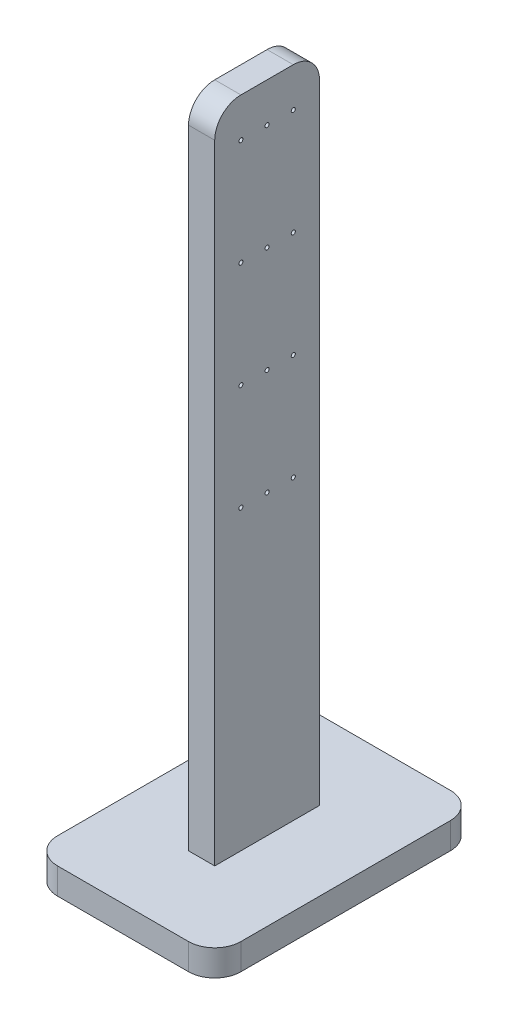
SolidWorks part; units mm, degrees
material "尼龙 101"
ref_plane "前视基准面" through (0, 0, 0) normal (0, 0, 1) x (1, 0, 0)
ref_plane "上视基准面" through (0, 0, 0) normal (0, 1, 0) x (1, 0, 0)
ref_plane "右视基准面" through (0, 0, 0) normal (1, 0, 0) x (0, 0, -1)
sketch "草图1" plane through (0, 0, 0) normal (1, 0, 0) x (0, 0, -1)
  line L1 (0, 0) -> (40, 0)
  line L2 (0, 0) -> (0, 240)
  line L3 (10, 250) -> (30, 250)
  line L4 (40, 0) -> (40, 240)
  circle A0 centre (10, 235) radius 0.7835
  circle A1 centre (20, 235) radius 0.7835
  circle A2 centre (30, 235) radius 0.7835
  arc A3 (30, 250) -> (40, 240) centre (30, 240) cw
  arc A4 (0, 240) -> (10, 250) centre (10, 240) cw
  circle A5 centre (10, 194.5) radius 0.7835
  circle A6 centre (20, 194.5) radius 0.7835
  circle A7 centre (30, 194.5) radius 0.7835
  circle A8 centre (10, 154) radius 0.7835
  circle A9 centre (20, 154) radius 0.7835
  circle A10 centre (30, 154) radius 0.7835
  circle A11 centre (10, 113.5) radius 0.7835
  circle A12 centre (20, 113.5) radius 0.7835
  circle A13 centre (30, 113.5) radius 0.7835
  point P17 (0, 250)
  dimension "D3" = 1.567
  dimension "D8" = 10
  dimension "D1" = 250
  dimension "D2" = 40
  dimension "D5" = 10
  dimension "D6" = 15
  dimension "D7" = 10
  dimension "D10" = 40.5
  dimension "D4" = 3
  dimension "D9" = 4
extrude "凸台-拉伸1" add sketch "草图1" along normal blind 10
cosmetic thread "装饰螺纹线1" parameters "D2"=2
cosmetic thread "装饰螺纹线2" parameters "D2"=2
cosmetic thread "装饰螺纹线3" parameters "D2"=2
cosmetic thread "装饰螺纹线4" parameters "D2"=2
cosmetic thread "装饰螺纹线5" parameters "D2"=2
cosmetic thread "装饰螺纹线6" parameters "D2"=2
cosmetic thread "装饰螺纹线7" parameters "D2"=2
cosmetic thread "装饰螺纹线8" parameters "D2"=2
cosmetic thread "装饰螺纹线9" parameters "D2"=2
cosmetic thread "装饰螺纹线10" parameters "D2"=2
cosmetic thread "装饰螺纹线11" parameters "D2"=2
cosmetic thread "装饰螺纹线12" parameters "D2"=2
sketch "草图2" plane through (0, 0, 0) normal (0, -1, 0) x (1, 0, 0)
  line L0 (10, 0) -> (0, 0) construction
  line L1 (-20, 30) -> (30, 30)
  line L2 (-30, 20) -> (-30, -60)
  line L3 (-20, -70) -> (30, -70)
  line L4 (40, 20) -> (40, -60)
  line L5 (10, 0) -> (10, -40) construction
  line L6 (0, 0) -> (0, -40) construction
  line L8 (10, -40) -> (0, -40) construction
  arc A0 (-30, -60) -> (-20, -70) centre (-20, -60) ccw
  arc A1 (30, -70) -> (40, -60) centre (30, -60) ccw
  arc A2 (30, 30) -> (40, 20) centre (30, 20) cw
  arc A3 (-20, 30) -> (-30, 20) centre (-20, 20) ccw
  dimension "D5" = 10
  dimension "D1" = 30
  dimension "D2" = 30
  dimension "D3" = 30
  dimension "D4" = 30
extrude "凸台-拉伸2" add sketch "草图2" along normal blind 10
